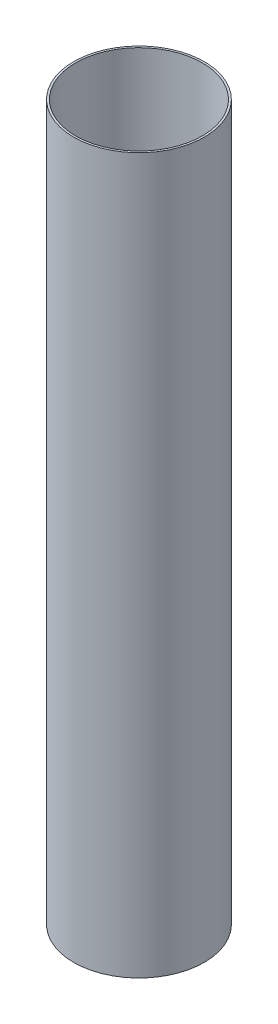
SolidWorks part; units mm, degrees
material "A-Glass Fiber"
ref_plane "Front Plane" through (0, 0, 0) normal (0, 0, 1) x (1, 0, 0)
ref_plane "Top Plane" through (0, 0, 0) normal (0, 1, 0) x (1, 0, 0)
ref_plane "Right Plane" through (0, 0, 0) normal (1, 0, 0) x (0, 0, -1)
sketch "Sketch1" plane through (0, 0, 0) normal (0, 1, 0) x (1, 0, 0)
  circle A0 centre (0, 0) radius 49.53
  circle A1 centre (0, 0) radius 51.1048
  dimension "D1" = 99.06
  dimension "D2" = 1.5748
extrude "Boss-Extrude1" add sketch "Sketch1" along normal blind 558.8
